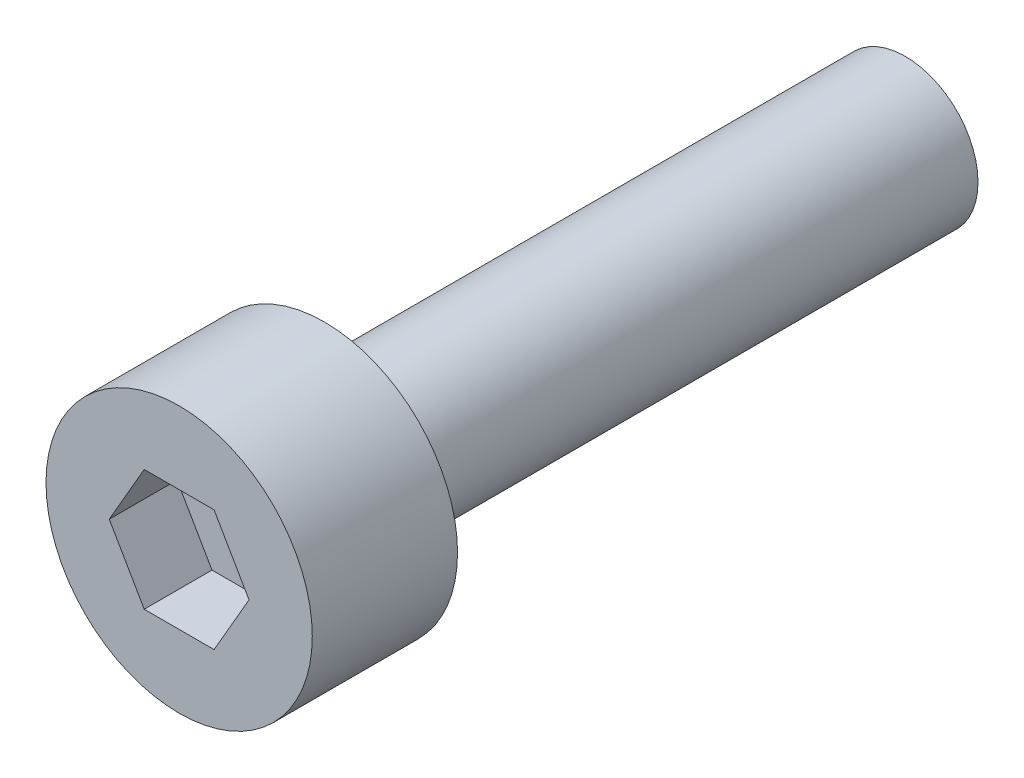
SolidWorks part; units mm, degrees
ref_plane "前视基准面" through (0, 0, 0) normal (0, 0, 1) x (1, 0, 0)
ref_plane "上视基准面" through (0, 0, 0) normal (0, 1, 0) x (1, 0, 0)
ref_plane "右视基准面" through (0, 0, 0) normal (1, 0, 0) x (0, 0, -1)
other "Configuration Table"
sketch "ISO4762_head_D5p5_h3_Sketch" plane through (0, 0, 0) normal (0, 0, 1) x (1, 0, 0)
  circle A0 centre (0, 0) radius 2.75
extrude "ISO4762_head_D5p5_h3" add sketch "ISO4762_head_D5p5_h3_Sketch" along normal blind 3 separate body
sketch "M3_major_diameter_envelope_Sketch" plane through (0, 0, 0) normal (0, 0, 1) x (1, 0, 0)
  circle A0 centre (0, 0) radius 1.5
extrude "M3_major_diameter_envelope" add sketch "M3_major_diameter_envelope_Sketch" along normal blind 12 from offset 12
sketch "Hex_socket_2p5AF_Sketch" plane through (0, 0, 0) normal (0, 0, 1) x (1, 0, 0)
  line L0 (1.4434, 0) -> (0.7217, 1.25)
  line L1 (0.7217, 1.25) -> (-0.7217, 1.25)
  line L2 (-0.7217, 1.25) -> (-1.4434, 0)
  line L3 (-1.4434, 0) -> (-0.7217, -1.25)
  line L4 (-0.7217, -1.25) -> (0.7217, -1.25)
  line L5 (0.7217, -1.25) -> (1.4434, 0)
extrude "Hex_socket_2p5AF" cut sketch "Hex_socket_2p5AF_Sketch" along normal blind 1.4 from offset 1.6
